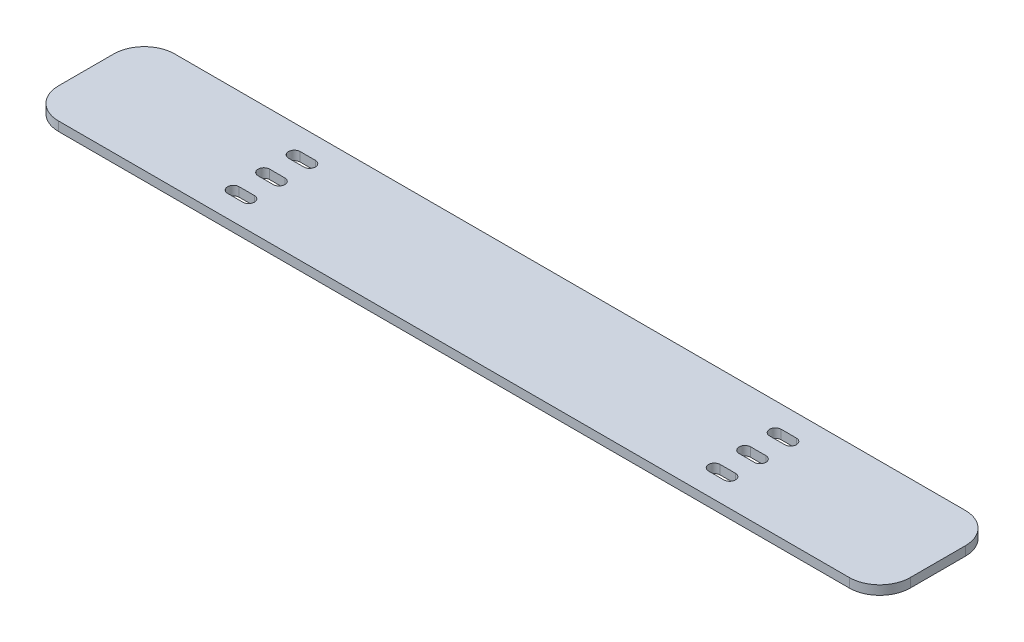
SolidWorks part; units mm, degrees
ref_plane "Front Plane" through (0, 0, 0) normal (0, 0, 1) x (1, 0, 0)
ref_plane "Top Plane" through (0, 0, 0) normal (0, 1, 0) x (1, 0, 0)
ref_plane "Right Plane" through (0, 0, 0) normal (1, 0, 0) x (0, 0, -1)
sketch "Sketch1" plane through (0, 0, 0) normal (0, 1, 0) x (1, 0, 0)
  line L1 (10, 0) -> (269.4, 0)
  line L2 (0, -10) -> (0, -28.1)
  line L3 (10, -38.1) -> (269.4, -38.1)
  line L4 (279.4, -10) -> (279.4, -28.1)
  arc A0 (0, -28.1) -> (10, -38.1) centre (10, -28.1) ccw
  arc A1 (269.4, -38.1) -> (279.4, -28.1) centre (269.4, -28.1) ccw
  arc A2 (269.4, 0) -> (279.4, -10) centre (269.4, -10) cw
  arc A3 (10, 0) -> (0, -10) centre (10, -10) ccw
  point P7 (0, -38.1)
  point P12 (279.4, 0)
  point P15 (0, 0)
  dimension "D3" = 10
  dimension "D1" = 279.4
  dimension "D2" = 38.1
extrude "Boss-Extrude1" add sketch "Sketch1" along normal blind 3
sketch "Sketch2" plane through (0, 3, 0) normal (0, 1, 0) x (1, 0, 0)
  line L0 (58.3, -19.05) -> (63.3, -19.05) construction
  line L1 (58.3, -17.15) -> (63.3, -17.15)
  line L2 (58.3, -20.95) -> (63.3, -20.95)
  line L3 (139.7, 0) -> (139.7, -38.1) construction
  line L4 (269.4, 0) -> (10, 0) construction
  line L5 (10, -38.1) -> (269.4, -38.1) construction
  line L6 (221.1, -19.05) -> (216.1, -19.05) construction
  line L7 (221.1, -17.15) -> (216.1, -17.15)
  line L8 (221.1, -20.95) -> (216.1, -20.95)
  line L9 (221.1, -27.15) -> (216.1, -27.15)
  line L10 (221.1, -30.95) -> (216.1, -30.95)
  line L11 (221.1, -29.05) -> (216.1, -29.05) construction
  line L12 (221.1, -7.15) -> (216.1, -7.15)
  line L13 (221.1, -10.95) -> (216.1, -10.95)
  line L14 (221.1, -9.05) -> (216.1, -9.05) construction
  line L15 (58.3, -29.05) -> (63.3, -29.05) construction
  line L16 (58.3, -27.15) -> (63.3, -27.15)
  line L17 (58.3, -30.95) -> (63.3, -30.95)
  line L18 (58.3, -9.05) -> (63.3, -9.05) construction
  line L19 (58.3, -7.15) -> (63.3, -7.15)
  line L20 (58.3, -10.95) -> (63.3, -10.95)
  arc A0 (58.3, -17.15) -> (58.3, -20.95) centre (58.3, -19.05) ccw
  arc A1 (63.3, -20.95) -> (63.3, -17.15) centre (63.3, -19.05) ccw
  arc A2 (221.1, -17.15) -> (221.1, -20.95) centre (221.1, -19.05) cw
  arc A3 (216.1, -20.95) -> (216.1, -17.15) centre (216.1, -19.05) cw
  arc A4 (216.1, -30.95) -> (216.1, -27.15) centre (216.1, -29.05) cw
  arc A5 (221.1, -27.15) -> (221.1, -30.95) centre (221.1, -29.05) cw
  arc A6 (216.1, -10.95) -> (216.1, -7.15) centre (216.1, -9.05) cw
  arc A7 (221.1, -7.15) -> (221.1, -10.95) centre (221.1, -9.05) cw
  arc A8 (58.3, -27.15) -> (58.3, -30.95) centre (58.3, -29.05) ccw
  arc A9 (63.3, -30.95) -> (63.3, -27.15) centre (63.3, -29.05) ccw
  arc A10 (58.3, -7.15) -> (58.3, -10.95) centre (58.3, -9.05) ccw
  arc A11 (63.3, -10.95) -> (63.3, -7.15) centre (63.3, -9.05) ccw
  point P2 (60.8, -19.05)
  point P13 (218.6, -9.05)
  point P15 (139.7, -19.05)
  point P18 (218.6, -19.05)
  point P24 (218.6, -29.05)
  point P32 (218.6, -9.05)
  point P38 (60.8, -29.05)
  point P45 (60.8, -9.05)
  dimension "D1" = 78.9
  dimension "D2" = 5
  dimension "D3" = 3.8
  dimension "D4" = 2
  dimension "D5" = 2
extrude "Cut-Extrude1" cut sketch "Sketch2" against normal up to next
